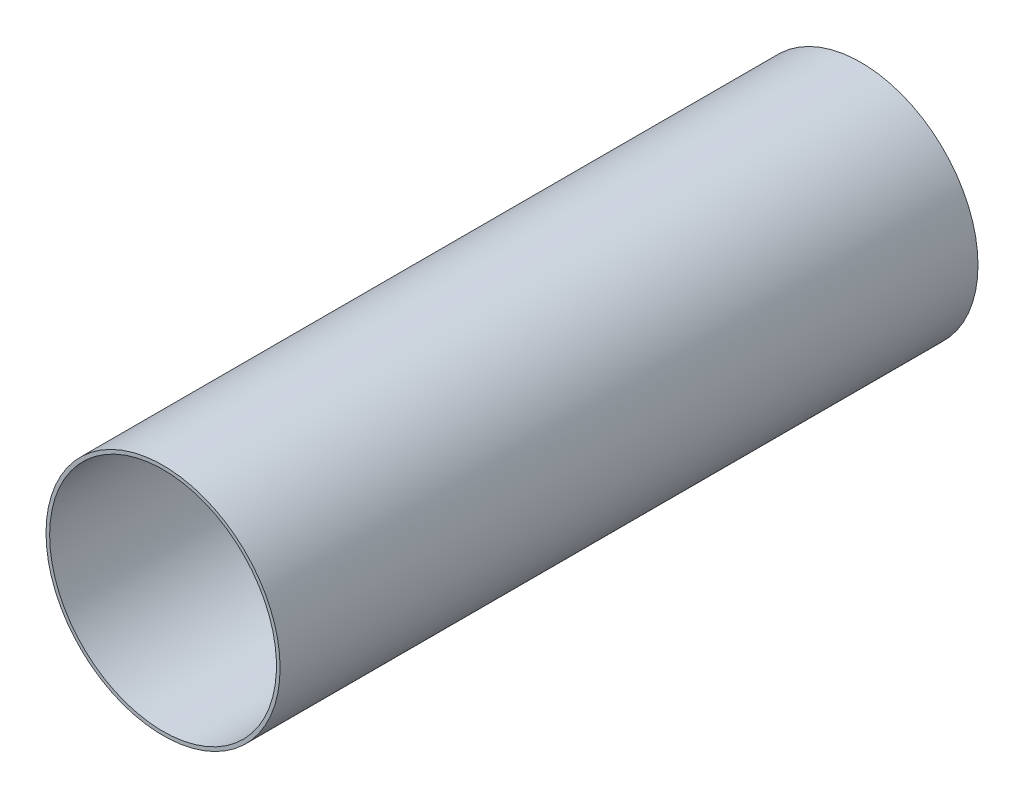
SolidWorks part; units mm, degrees
material "Thornel Mat VMA"
ref_plane "Front Plane" through (0, 0, 0) normal (0, 0, 1) x (1, 0, 0)
ref_plane "Top Plane" through (0, 0, 0) normal (0, 1, 0) x (1, 0, 0)
ref_plane "Right Plane" through (0, 0, 0) normal (1, 0, 0) x (0, 0, -1)
sketch "Sketch1" plane through (0, 0, 0) normal (0, 0, 1) x (1, 0, 0)
  circle A0 centre (0, 0) radius 51.1175
  circle A1 centre (0, 0) radius 49.53
  dimension "D1" = 1.5875
  dimension "D2" = 102.235
extrude "Boss-Extrude1" add sketch "Sketch1" along normal blind 304.8
